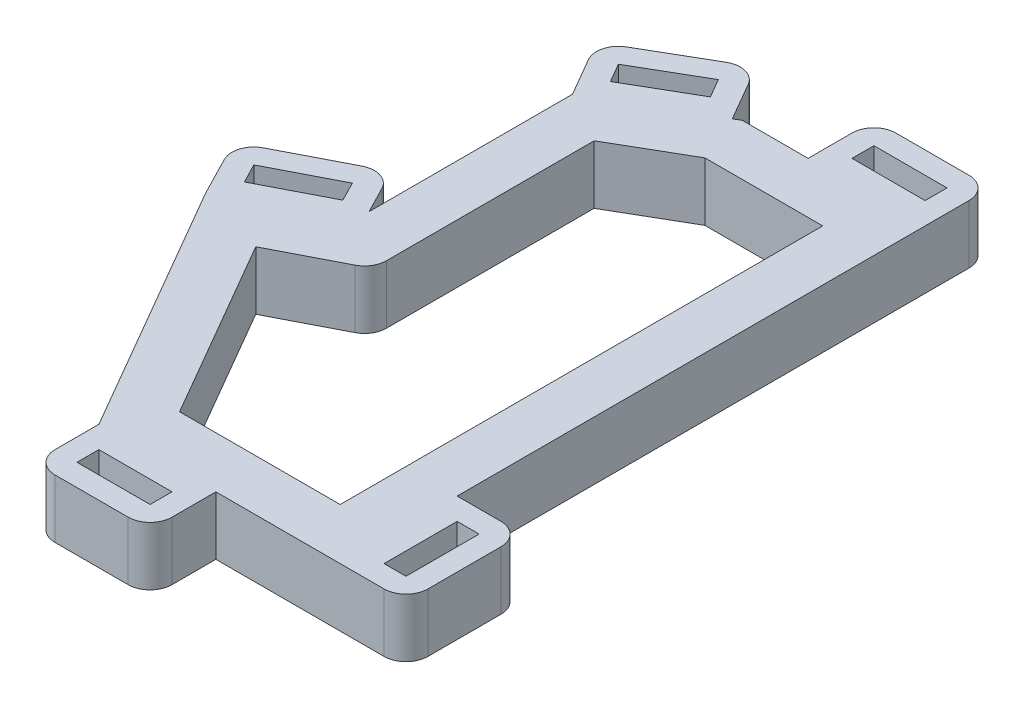
SolidWorks part; units mm, degrees
ref_plane "Front Plane" through (0, 0, 0) normal (0, 0, 1) x (1, 0, 0)
ref_plane "Top Plane" through (0, 0, 0) normal (0, 1, 0) x (1, 0, 0)
ref_plane "Right Plane" through (0, 0, 0) normal (1, 0, 0) x (0, 0, -1)
sketch "Sketch1" plane through (0, 0, 0) normal (0, 1, 0) x (1, 0, 0)
  line L8 (-25, 0) -> (0, 0)
  line L9 (0, 0) -> (0, -80)
  line L10 (0, -80) -> (-33, -80)
  line L11 (-33, -80) -> (-53.0471, -45.3862)
  line L12 (-53.0471, -45.3862) -> (-39.7109, -38.52)
  line L13 (-39.7109, -38.52) -> (-39.7109, -8.52)
  line L14 (-39.7109, -8.52) -> (-25, 0)
  line L15 (-23.1193, -7) -> (-7, -7)
  line L16 (-7, -7) -> (-7, -73)
  line L17 (-7, -73) -> (-28.9649, -73)
  line L18 (-28.9649, -73) -> (-43.3033, -48.2429)
  line L19 (-43.3033, -48.2429) -> (-32.7109, -42.7893)
  line L20 (-32.7109, -42.7893) -> (-32.7109, -12.5551)
  line L21 (-32.7109, -12.5551) -> (-23.1193, -7)
  dimension "D1" = 25
  dimension "D2" = 80
  dimension "D3" = 33
  dimension "D4" = 40
  dimension "D5" = 15
  dimension "D6" = 30
  dimension "D7" = 17
  dimension "D8" = 7
extrude "Boss-Extrude1" add sketch "Sketch1" along normal blind 8
sketch "Sketch2" plane through (0, 0, 0) normal (0, 1, 0) x (1, 0, 0)
  line L6 (-53.0471, -45.3862) -> (-38.8218, -38.0623)
  line L7 (-53.0471, -45.3862) -> (-57.1668, -37.3845)
  line L8 (-38.8218, -38.0623) -> (-42.9415, -30.0605)
  line L9 (-57.1668, -37.3845) -> (-42.9415, -30.0605)
  line L10 (-39.7109, -38.52) -> (-53.0471, -45.3862) construction
  line L11 (-39.7109, -8.52) -> (-25.8653, -0.5012)
  line L12 (-39.7109, -8.52) -> (-44.2215, -0.7319)
  line L13 (-25.8653, -0.5012) -> (-30.3759, 7.2869)
  line L14 (-44.2215, -0.7319) -> (-30.3759, 7.2869)
  line L16 (-16, 0) -> (0, 0)
  line L17 (-16, 0) -> (-16, 9)
  line L18 (0, 0) -> (0, 9)
  line L19 (-16, 9) -> (0, 9)
  line L21 (-25, 0) -> (-39.7109, -8.52) construction
  line L24 (0, 0) -> (-25, 0) construction
  line L25 (-51.7531, -41.3457) -> (-42.8623, -36.7683)
  line L26 (-42.8623, -36.7683) -> (-44.2355, -34.101)
  line L27 (-53.1263, -38.6785) -> (-44.2355, -34.101)
  line L28 (-51.7531, -41.3457) -> (-53.1263, -38.6785)
  line L29 (-38.6184, -4.4205) -> (-29.9649, 0.5913)
  line L30 (-29.9649, 0.5913) -> (-31.4684, 3.1874)
  line L31 (-40.1219, -1.8244) -> (-31.4684, 3.1874)
  line L32 (-38.6184, -4.4205) -> (-40.1219, -1.8244)
  line L33 (-13, 3) -> (-3, 3)
  line L34 (-3, 3) -> (-3, 6)
  line L35 (-13, 6) -> (-3, 6)
  line L36 (-13, 3) -> (-13, 6)
  line L42 (-33, -80) -> (-17, -80)
  line L43 (-33, -80) -> (-33, -89)
  line L44 (-17, -80) -> (-17, -89)
  line L45 (-33, -89) -> (-17, -89)
  line L46 (-33, -80) -> (0, -80) construction
  line L47 (0, -80) -> (0, -64)
  line L48 (0, -80) -> (9, -80)
  line L49 (0, -64) -> (9, -64)
  line L50 (9, -80) -> (9, -64)
  line L51 (0, -80) -> (0, 0) construction
  line L52 (-30, -83) -> (-20, -83)
  line L53 (-20, -83) -> (-20, -86)
  line L54 (-30, -86) -> (-20, -86)
  line L55 (-30, -83) -> (-30, -86)
  line L56 (3, -77) -> (3, -67)
  line L57 (3, -67) -> (6, -67)
  line L58 (6, -77) -> (6, -67)
  line L59 (3, -77) -> (6, -77)
  dimension "D1" = 16
  dimension "D2" = 9
  dimension "D3" = 3
  dimension "D4" = 3
extrude "Boss-Extrude2" add sketch "Sketch2" along normal up to surface (8 mm away) up to face at (-27.2098, 8, 36.0609)
fillet "Fillet1" radius 3 11 edges at (0, 4, -9) (-16, 4, -9) (-30.3759, 4, -7.2869) (-44.2215, 4, 0.7319) (-42.9415, 4, 30.0605) (-57.1668, 4, 37.3845) (-32.7109, 4, 42.7893) (9, 4, 64) (9, 4, 80) (-33, 4, 89) (-17, 4, 89)
